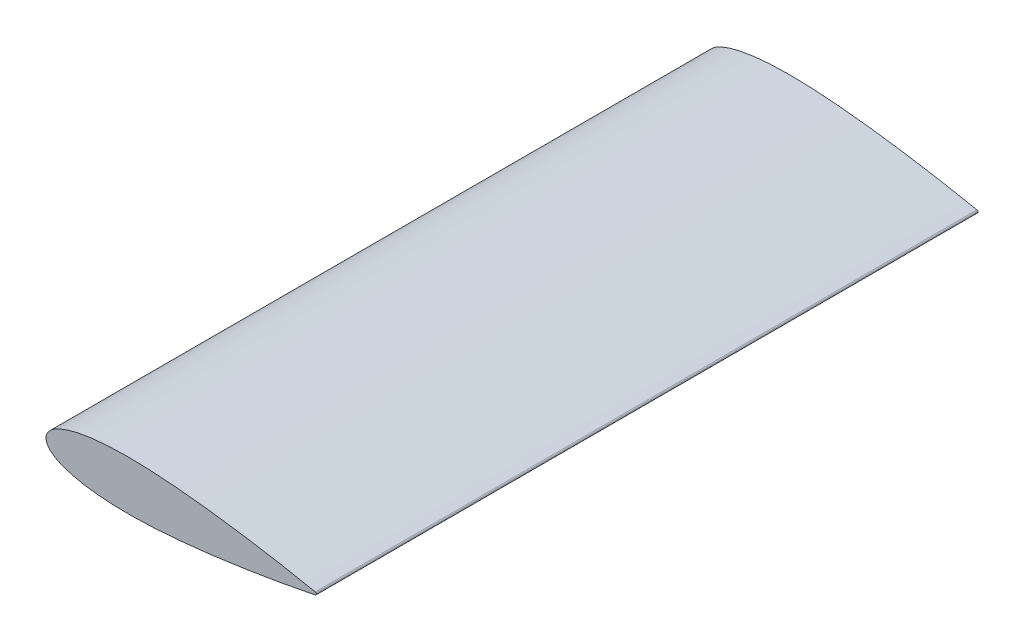
SolidWorks part; units mm, degrees
material "Polyurethane Foam Rigid"
ref_plane "Front Plane" through (0, 0, 0) normal (0, 0, 1) x (1, 0, 0)
ref_plane "Top Plane" through (0, 0, 0) normal (0, 1, 0) x (1, 0, 0)
ref_plane "Right Plane" through (0, 0, 0) normal (1, 0, 0) x (0, 0, -1)
curve "Curve1"
  spline degree 3 poles (0.9998, 0, 0) (1.0001, 0, 0) (0.9998, 0, 0) (0.9995, 0.0001, 0) (0.9989, 0.0002, 0) (0.9982, 0.0004, 0) (0.9972, 0.0006, 0) (0.996, 0.0009, 0) (0.9946, 0.0012, 0) (0.9929, 0.0015, 0) (0.9911, 0.0019, 0) (0.989, 0.0023, 0) (0.9867, 0.0028, 0) (0.9842, 0.0033, 0) (0.9815, 0.0039, 0) (0.9786, 0.0045, 0) (0.9755, 0.0051, 0) (0.9721, 0.0058, 0) (0.9686, 0.0065, 0) (0.9648, 0.0073, 0) (0.9609, 0.0081, 0) (0.9567, 0.009, 0) (0.9523, 0.0098, 0) (0.9478, 0.0107, 0) (0.943, 0.0117, 0) (0.9381, 0.0127, 0) (0.9329, 0.0137, 0) (0.9276, 0.0147, 0) (0.9221, 0.0158, 0) (0.9164, 0.0169, 0) (0.9105, 0.018, 0) (0.9045, 0.0192, 0) (0.8982, 0.0204, 0) (0.8918, 0.0216, 0) (0.8852, 0.0228, 0) (0.8784, 0.024, 0) (0.8715, 0.0253, 0) (0.8644, 0.0266, 0) (0.8572, 0.0279, 0) (0.8498, 0.0292, 0) (0.8422, 0.0306, 0) (0.8345, 0.0319, 0) (0.8267, 0.0333, 0) (0.8187, 0.0347, 0) (0.8105, 0.0361, 0) (0.8023, 0.0375, 0) (0.7939, 0.0389, 0) (0.7853, 0.0403, 0) (0.7767, 0.0417, 0) (0.7679, 0.0431, 0) (0.759, 0.0446, 0) (0.75, 0.046, 0) (0.7408, 0.0474, 0) (0.7316, 0.0489, 0) (0.7223, 0.0503, 0) (0.7129, 0.0517, 0) (0.7033, 0.0531, 0) (0.6937, 0.0546, 0) (0.684, 0.056, 0) (0.6743, 0.0574, 0) (0.6644, 0.0588, 0) (0.6545, 0.0601, 0) (0.6445, 0.0615, 0) (0.6344, 0.0629, 0) (0.6243, 0.0642, 0) (0.6142, 0.0655, 0) (0.6039, 0.0668, 0) (0.5937, 0.0681, 0) (0.5834, 0.0694, 0) (0.573, 0.0706, 0) (0.5627, 0.0718, 0) (0.5523, 0.073, 0) (0.5418, 0.0742, 0) (0.5314, 0.0753, 0) (0.5209, 0.0764, 0) (0.5105, 0.0774, 0) (0.5, 0.0785, 0) (0.4895, 0.0795, 0) (0.4791, 0.0804, 0) (0.4686, 0.0813, 0) (0.4582, 0.0822, 0) (0.4477, 0.083, 0) (0.4373, 0.0838, 0) (0.427, 0.0846, 0) (0.4166, 0.0853, 0) (0.4063, 0.0859, 0) (0.3961, 0.0865, 0) (0.3858, 0.0871, 0) (0.3757, 0.0876, 0) (0.3656, 0.088, 0) (0.3555, 0.0884, 0) (0.3455, 0.0887, 0) (0.3356, 0.089, 0) (0.3257, 0.0892, 0) (0.316, 0.0894, 0) (0.3063, 0.0894, 0) (0.2967, 0.0895, 0) (0.2871, 0.0894, 0) (0.2777, 0.0893, 0) (0.2684, 0.0892, 0) (0.2592, 0.089, 0) (0.25, 0.0887, 0) (0.241, 0.0883, 0) (0.2321, 0.0879, 0) (0.2233, 0.0874, 0) (0.2147, 0.0868, 0) (0.2061, 0.0862, 0) (0.1977, 0.0855, 0) (0.1895, 0.0847, 0) (0.1813, 0.0839, 0) (0.1733, 0.083, 0) (0.1655, 0.0821, 0) (0.1578, 0.081, 0) (0.1502, 0.0799, 0) (0.1428, 0.0788, 0) (0.1356, 0.0776, 0) (0.1285, 0.0763, 0) (0.1215, 0.0749, 0) (0.1148, 0.0735, 0) (0.1082, 0.072, 0) (0.1018, 0.0705, 0) (0.0955, 0.0689, 0) (0.0895, 0.0673, 0) (0.0836, 0.0656, 0) (0.0779, 0.0638, 0) (0.0724, 0.062, 0) (0.067, 0.0601, 0) (0.0619, 0.0582, 0) (0.0569, 0.0562, 0) (0.0522, 0.0542, 0) (0.0476, 0.0522, 0) (0.0433, 0.05, 0) (0.0391, 0.0479, 0) (0.0351, 0.0457, 0) (0.0314, 0.0434, 0) (0.0278, 0.0412, 0) (0.0245, 0.0388, 0) (0.0214, 0.0365, 0) (0.0184, 0.0341, 0) (0.0157, 0.0317, 0) (0.0132, 0.0292, 0) (0.0109, 0.0267, 0) (0.0089, 0.0241, 0) (0.007, 0.0216, 0) (0.0053, 0.019, 0) (0.0039, 0.0164, 0) (0.0027, 0.0137, 0) (0.0017, 0.011, 0) (0.001, 0.0083, 0) (0.0004, 0.0056, 0) (0.0001, 0.0028, 0) (0, 0, 0) (0.0001, -0.0028, 0) (0.0004, -0.0056, 0) (0.001, -0.0083, 0) (0.0017, -0.011, 0) (0.0027, -0.0137, 0) (0.0039, -0.0164, 0) (0.0053, -0.019, 0) (0.007, -0.0216, 0) (0.0089, -0.0241, 0) (0.0109, -0.0267, 0) (0.0132, -0.0292, 0) (0.0157, -0.0317, 0) (0.0184, -0.0341, 0) (0.0214, -0.0365, 0) (0.0245, -0.0388, 0) (0.0278, -0.0412, 0) (0.0314, -0.0434, 0) (0.0351, -0.0457, 0) (0.0391, -0.0479, 0) (0.0433, -0.05, 0) (0.0476, -0.0522, 0) (0.0522, -0.0542, 0) (0.0569, -0.0562, 0) (0.0619, -0.0582, 0) (0.067, -0.0601, 0) (0.0724, -0.062, 0) (0.0779, -0.0638, 0) (0.0836, -0.0656, 0) (0.0895, -0.0673, 0) (0.0955, -0.0689, 0) (0.1018, -0.0705, 0) (0.1082, -0.072, 0) (0.1148, -0.0735, 0) (0.1215, -0.0749, 0) (0.1285, -0.0763, 0) (0.1356, -0.0776, 0) (0.1428, -0.0788, 0) (0.1502, -0.0799, 0) (0.1578, -0.081, 0) (0.1655, -0.0821, 0) (0.1733, -0.083, 0) (0.1813, -0.0839, 0) (0.1895, -0.0847, 0) (0.1977, -0.0855, 0) (0.2061, -0.0862, 0) (0.2147, -0.0868, 0) (0.2233, -0.0874, 0) (0.2321, -0.0879, 0) (0.241, -0.0883, 0) (0.25, -0.0887, 0) (0.2592, -0.089, 0) (0.2684, -0.0892, 0) (0.2777, -0.0893, 0) (0.2871, -0.0894, 0) (0.2967, -0.0895, 0) (0.3063, -0.0894, 0) (0.316, -0.0894, 0) (0.3257, -0.0892, 0) (0.3356, -0.089, 0) (0.3455, -0.0887, 0) (0.3555, -0.0884, 0) (0.3656, -0.088, 0) (0.3757, -0.0876, 0) (0.3858, -0.0871, 0) (0.3961, -0.0865, 0) (0.4063, -0.0859, 0) (0.4166, -0.0853, 0) (0.427, -0.0846, 0) (0.4373, -0.0838, 0) (0.4477, -0.083, 0) (0.4582, -0.0822, 0) (0.4686, -0.0813, 0) (0.4791, -0.0804, 0) (0.4895, -0.0795, 0) (0.5, -0.0785, 0) (0.5105, -0.0774, 0) (0.5209, -0.0764, 0) (0.5314, -0.0753, 0) (0.5418, -0.0742, 0) (0.5523, -0.073, 0) (0.5627, -0.0718, 0) (0.573, -0.0706, 0) (0.5834, -0.0694, 0) (0.5937, -0.0681, 0) (0.6039, -0.0668, 0) (0.6142, -0.0655, 0) (0.6243, -0.0642, 0) (0.6344, -0.0629, 0) (0.6445, -0.0615, 0) (0.6545, -0.0601, 0) (0.6644, -0.0588, 0) (0.6743, -0.0574, 0) (0.684, -0.056, 0) (0.6937, -0.0546, 0) (0.7033, -0.0531, 0) (0.7129, -0.0517, 0) (0.7223, -0.0503, 0) (0.7316, -0.0489, 0) (0.7408, -0.0474, 0) (0.75, -0.046, 0) (0.759, -0.0446, 0) (0.7679, -0.0431, 0) (0.7767, -0.0417, 0) (0.7853, -0.0403, 0) (0.7939, -0.0389, 0) (0.8023, -0.0375, 0) (0.8105, -0.0361, 0) (0.8187, -0.0347, 0) (0.8267, -0.0333, 0) (0.8345, -0.0319, 0) (0.8422, -0.0306, 0) (0.8498, -0.0292, 0) (0.8572, -0.0279, 0) (0.8644, -0.0266, 0) (0.8715, -0.0253, 0) (0.8784, -0.024, 0) (0.8852, -0.0228, 0) (0.8918, -0.0216, 0) (0.8982, -0.0204, 0) (0.9045, -0.0192, 0) (0.9105, -0.018, 0) (0.9164, -0.0169, 0) (0.9221, -0.0158, 0) (0.9276, -0.0147, 0) (0.9329, -0.0137, 0) (0.9381, -0.0127, 0) (0.943, -0.0117, 0) (0.9478, -0.0107, 0) (0.9523, -0.0098, 0) (0.9567, -0.009, 0) (0.9609, -0.0081, 0) (0.9648, -0.0073, 0) (0.9686, -0.0065, 0) (0.9721, -0.0058, 0) (0.9755, -0.0051, 0) (0.9786, -0.0045, 0) (0.9815, -0.0039, 0) (0.9842, -0.0033, 0) (0.9867, -0.0028, 0) (0.989, -0.0023, 0) (0.9911, -0.0019, 0) (0.9929, -0.0015, 0) (0.9946, -0.0012, 0) (0.996, -0.0009, 0) (0.9972, -0.0006, 0) (0.9982, -0.0004, 0) (0.9989, -0.0002, 0) (0.9995, -0.0001, 0) (0.9998, 0, 0) (1.0001, 0, 0) (0.9998, 0, 0) knots -0.000486 -0.000216 -0.000054 0 0.000054 0.000216 0.000486 0.000863 0.001349 0.001941 0.002641 0.003447 0.00436 0.005379 0.006503 0.007732 0.009066 0.010503 0.012043 0.013685 0.01543 0.017274 0.019219 0.021263 0.023405 0.025644 0.027978 0.030408 0.032932 0.035548 0.038256 0.041054 0.04394 0.046915 0.049975 0.053121 0.05635 0.059661 0.063052 0.066522 0.07007 0.073693 0.077391 0.08116 0.085001 0.088911 0.092888 0.09693 0.101036 0.105204 0.109431 0.113717 0.118059 0.122455 0.126904 0.131403 0.135949 0.140543 0.14518 0.149859 0.154579 0.159336 0.164129 0.168955 0.173814 0.178701 0.183616 0.188555 0.193518 0.198501 0.203502 0.20852 0.213551 0.218594 0.223647 0.228706 0.233771 0.238839 0.243907 0.248973 0.254036 0.259092 0.26414 0.269178 0.274203 0.279214 0.284207 0.289181 0.294134 0.299064 0.303968 0.308845 0.313692 0.318508 0.323291 0.328038 0.332747 0.337418 0.342047 0.346633 0.351175 0.35567 0.360116 0.364513 0.368858 0.37315 0.377387 0.381568 0.38569 0.389754 0.393756 0.397696 0.401573 0.405385 0.409131 0.412809 0.41642 0.41996 0.42343 0.426829 0.430155 0.433407 0.436586 0.439689 0.442717 0.445669 0.448545 0.451343 0.454064 0.456707 0.459273 0.461761 0.464171 0.466505 0.468761 0.470942 0.473048 0.47508 0.47704 0.478929 0.480749 0.482504 0.484195 0.485826 0.487402 0.488926 0.490404 0.491842 0.493245 0.49462 0.495975 0.497318 0.498657 0.5 0.501343 0.502682 0.504025 0.50538 0.506755 0.508158 0.509596 0.511074 0.512598 0.514174 0.515805 0.517496 0.519251 0.521071 0.52296 0.52492 0.526952 0.529058 0.531239 0.533495 0.535829 0.538239 0.540727 0.543293 0.545936 0.548657 0.551455 0.554331 0.557283 0.560311 0.563414 0.566593 0.569845 0.573171 0.57657 0.58004 0.58358 0.587191 0.590869 0.594615 0.598427 0.602304 0.606244 0.610246 0.61431 0.618432 0.622613 0.62685 0.631142 0.635487 0.639884 0.64433 0.648825 0.653367 0.657953 0.662582 0.667253 0.671962 0.676709 0.681492 0.686308 0.691155 0.696032 0.700936 0.705866 0.710819 0.715793 0.720786 0.725797 0.730822 0.73586 0.740908 0.745964 0.751027 0.756093 0.761161 0.766229 0.771294 0.776353 0.781406 0.786449 0.79148 0.796498 0.801499 0.806482 0.811445 0.816384 0.821299 0.826186 0.831045 0.835871 0.840664 0.845421 0.850141 0.85482 0.859457 0.864051 0.868597 0.873096 0.877545 0.881941 0.886283 0.890569 0.894796 0.898964 0.90307 0.907112 0.911089 0.914999 0.91884 0.922609 0.926307 0.92993 0.933478 0.936948 0.940339 0.94365 0.946879 0.950025 0.953085 0.95606 0.958946 0.961744 0.964452 0.967068 0.969592 0.972022 0.974356 0.976595 0.978737 0.980781 0.982726 0.98457 0.986315 0.987957 0.989497 0.990934 0.992268 0.993497 0.994621 0.99564 0.996553 0.997359 0.998059 0.998651 0.999137 0.999514 0.999784 0.999946 1 1.000054 1.000216 1.000486 periodic
sketch "Sketch1" plane through (0, 0, 0) normal (0, 0, 1) x (1, 0, 0)
  line L0 (500, 0) -> (0, 0) construction
  line L1 (0, 0) -> (0, 42.6879) construction
  spline S1 degree 3 poles (499.8824, -0.0194) (500.0294, 0) (499.8824, 0.0194) (499.761, 0.0543) (499.4625, 0.1124) (499.0899, 0.1937) (498.593, 0.2981) (497.9928, 0.4253) (497.2818, 0.5753) (496.4631, 0.7479) (495.5359, 0.9429) (494.5012, 1.16) (493.3592, 1.3989) (492.1105, 1.6595) (490.7555, 1.9413) (489.295, 2.244) (487.7295, 2.5673) (486.0597, 2.9109) (484.2864, 3.2742) (482.4103, 3.6569) (480.4323, 4.0585) (478.3532, 4.4786) (476.1739, 4.9168) (473.8954, 5.3725) (471.5188, 5.8452) (469.0449, 6.3344) (466.475, 6.8397) (463.8101, 7.3605) (461.0514, 7.8961) (458.2002, 8.4462) (455.2576, 9.0101) (452.2251, 9.5872) (449.1038, 10.177) (445.8951, 10.7789) (442.6006, 11.3923) (439.2215, 12.0167) (435.7595, 12.6514) (432.216, 13.2958) (428.5925, 13.9493) (424.8908, 14.6114) (421.1123, 15.2814) (417.2587, 15.9587) (413.3318, 16.6427) (409.3332, 17.3328) (405.2648, 18.0283) (401.1282, 18.7287) (396.9254, 19.4333) (392.6581, 20.1415) (388.3283, 20.8527) (383.9377, 21.5662) (379.4884, 22.2814) (374.9824, 22.9977) (370.4215, 23.7144) (365.8077, 24.4308) (361.1432, 25.1463) (356.4299, 25.8603) (351.67, 26.572) (346.8654, 27.2807) (342.0184, 27.9859) (337.131, 28.6868) (332.2054, 29.3827) (327.2437, 30.0728) (322.2481, 30.7566) (317.2209, 31.4332) (312.1642, 32.102) (307.0802, 32.7621) (301.9711, 33.4128) (296.8393, 34.0535) (291.6869, 34.6832) (286.5163, 35.3013) (281.3296, 35.907) (276.1291, 36.4994) (270.9173, 37.0778) (265.6962, 37.6415) (260.4682, 38.1895) (255.2357, 38.7211) (250.0009, 39.2356) (244.766, 39.7321) (239.5335, 40.2097) (234.3055, 40.6678) (229.0844, 41.1056) (223.8725, 41.5221) (218.6721, 41.9167) (213.4854, 42.2886) (208.3147, 42.6371) (203.1622, 42.9613) (198.0304, 43.2606) (192.9213, 43.5343) (187.8372, 43.7816) (182.7804, 44.0019) (177.7531, 44.1945) (172.7575, 44.3588) (167.7957, 44.4943) (162.87, 44.6003) (157.9825, 44.6762) (153.1354, 44.7217) (148.3307, 44.7361) (143.5706, 44.7192) (138.8572, 44.6704) (134.1926, 44.5894) (129.5787, 44.4759) (125.0176, 44.3295) (120.5114, 44.1502) (116.0619, 43.9375) (111.6712, 43.6915) (107.3412, 43.412) (103.0737, 43.0988) (98.8706, 42.7521) (94.7338, 42.3718) (90.6651, 41.9579) (86.6663, 41.5107) (82.7391, 41.0302) (78.8853, 40.5167) (75.1065, 39.9703) (71.4044, 39.3915) (67.7806, 38.7805) (64.2367, 38.1376) (60.7743, 37.4633) (57.3948, 36.758) (54.0998, 36.0223) (50.8907, 35.2565) (47.7689, 34.4613) (44.7357, 33.6371) (41.7926, 32.7847) (38.9407, 31.9045) (36.1813, 30.9972) (33.5157, 30.0636) (30.9449, 29.1041) (28.4702, 28.1196) (26.0925, 27.1107) (23.813, 26.078) (21.6325, 25.0223) (19.5521, 23.9442) (17.5726, 22.8444) (15.695, 21.7236) (13.9199, 20.5824) (12.2482, 19.4215) (10.6806, 18.2415) (9.2178, 17.0429) (7.8604, 15.8264) (6.609, 14.5925) (5.4642, 13.3416) (4.4265, 12.0743) (3.4965, 10.7909) (2.6745, 9.4919) (1.9611, 8.1778) (1.3567, 6.8488) (0.8617, 5.5055) (0.4765, 4.1481) (0.2013, 2.7771) (0.0363, 1.3928) (-0.0182, 0) (0.0363, -1.3928) (0.2013, -2.7771) (0.4765, -4.1481) (0.8617, -5.5055) (1.3567, -6.8488) (1.9611, -8.1778) (2.6745, -9.4919) (3.4965, -10.7909) (4.4265, -12.0743) (5.4642, -13.3416) (6.609, -14.5925) (7.8604, -15.8264) (9.2178, -17.0429) (10.6806, -18.2415) (12.2482, -19.4215) (13.9199, -20.5824) (15.695, -21.7236) (17.5726, -22.8444) (19.5521, -23.9442) (21.6325, -25.0223) (23.813, -26.078) (26.0925, -27.1107) (28.4702, -28.1196) (30.9449, -29.1041) (33.5157, -30.0636) (36.1813, -30.9972) (38.9407, -31.9045) (41.7926, -32.7847) (44.7357, -33.6371) (47.7689, -34.4613) (50.8907, -35.2565) (54.0998, -36.0223) (57.3948, -36.758) (60.7743, -37.4633) (64.2367, -38.1376) (67.7806, -38.7805) (71.4044, -39.3915) (75.1065, -39.9703) (78.8853, -40.5167) (82.7391, -41.0302) (86.6663, -41.5107) (90.6651, -41.9579) (94.7338, -42.3718) (98.8706, -42.7521) (103.0737, -43.0988) (107.3412, -43.412) (111.6712, -43.6915) (116.0619, -43.9375) (120.5114, -44.1502) (125.0176, -44.3295) (129.5787, -44.4759) (134.1926, -44.5894) (138.8572, -44.6704) (143.5706, -44.7192) (148.3307, -44.7361) (153.1354, -44.7217) (157.9825, -44.6762) (162.87, -44.6003) (167.7957, -44.4943) (172.7575, -44.3588) (177.7531, -44.1945) (182.7804, -44.0019) (187.8372, -43.7816) (192.9213, -43.5343) (198.0304, -43.2606) (203.1622, -42.9613) (208.3147, -42.6371) (213.4854, -42.2886) (218.6721, -41.9167) (223.8725, -41.5221) (229.0844, -41.1056) (234.3055, -40.6678) (239.5335, -40.2097) (244.766, -39.7321) (250.0009, -39.2356) (255.2357, -38.7211) (260.4682, -38.1895) (265.6962, -37.6415) (270.9173, -37.0778) (276.1291, -36.4994) (281.3296, -35.907) (286.5163, -35.3013) (291.6869, -34.6832) (296.8393, -34.0535) (301.9711, -33.4128) (307.0802, -32.7621) (312.1642, -32.102) (317.2209, -31.4332) (322.2481, -30.7566) (327.2437, -30.0728) (332.2054, -29.3827) (337.131, -28.6868) (342.0184, -27.9859) (346.8654, -27.2807) (351.67, -26.572) (356.4299, -25.8603) (361.1432, -25.1463) (365.8077, -24.4308) (370.4215, -23.7144) (374.9824, -22.9977) (379.4884, -22.2814) (383.9377, -21.5662) (388.3283, -20.8527) (392.6581, -20.1415) (396.9254, -19.4333) (401.1282, -18.7287) (405.2648, -18.0283) (409.3332, -17.3328) (413.3318, -16.6427) (417.2587, -15.9587) (421.1123, -15.2814) (424.8908, -14.6114) (428.5925, -13.9493) (432.216, -13.2958) (435.7595, -12.6514) (439.2215, -12.0167) (442.6006, -11.3923) (445.8951, -10.7789) (449.1038, -10.177) (452.2251, -9.5872) (455.2576, -9.0101) (458.2002, -8.4462) (461.0514, -7.8961) (463.8101, -7.3605) (466.475, -6.8397) (469.0449, -6.3344) (471.5188, -5.8452) (473.8954, -5.3725) (476.1739, -4.9168) (478.3532, -4.4786) (480.4323, -4.0585) (482.4103, -3.6569) (484.2864, -3.2742) (486.0597, -2.9109) (487.7295, -2.5673) (489.295, -2.244) (490.7555, -1.9413) (492.1105, -1.6595) (493.3592, -1.3989) (494.5012, -1.16) (495.5359, -0.9429) (496.4631, -0.7479) (497.2818, -0.5753) (497.9928, -0.4253) (498.593, -0.2981) (499.0899, -0.1937) (499.4625, -0.1124) (499.761, -0.0543) (499.8824, -0.0194) (500.0294, 0) (499.8824, 0.0194) knots -0.000486 -0.000216 -0.000054 0 0.000054 0.000216 0.000486 0.000863 0.001349 0.001941 0.002641 0.003447 0.00436 0.005379 0.006503 0.007732 0.009066 0.010503 0.012043 0.013685 0.01543 0.017274 0.019219 0.021263 0.023405 0.025644 0.027978 0.030408 0.032932 0.035548 0.038256 0.041054 0.04394 0.046915 0.049975 0.053121 0.05635 0.059661 0.063052 0.066522 0.07007 0.073693 0.077391 0.08116 0.085001 0.088911 0.092888 0.09693 0.101036 0.105204 0.109431 0.113717 0.118059 0.122455 0.126904 0.131403 0.135949 0.140543 0.14518 0.149859 0.154579 0.159336 0.164129 0.168955 0.173814 0.178701 0.183616 0.188555 0.193518 0.198501 0.203502 0.20852 0.213551 0.218594 0.223647 0.228706 0.233771 0.238839 0.243907 0.248973 0.254036 0.259092 0.26414 0.269178 0.274203 0.279214 0.284207 0.289181 0.294134 0.299064 0.303968 0.308845 0.313692 0.318508 0.323291 0.328038 0.332747 0.337418 0.342047 0.346633 0.351175 0.35567 0.360116 0.364513 0.368858 0.37315 0.377387 0.381568 0.38569 0.389754 0.393756 0.397696 0.401573 0.405385 0.409131 0.412809 0.41642 0.41996 0.42343 0.426829 0.430155 0.433407 0.436586 0.439689 0.442717 0.445669 0.448545 0.451343 0.454064 0.456707 0.459273 0.461761 0.464171 0.466505 0.468761 0.470942 0.473048 0.47508 0.47704 0.478929 0.480749 0.482504 0.484195 0.485826 0.487402 0.488926 0.490404 0.491842 0.493245 0.49462 0.495975 0.497318 0.498657 0.5 0.501343 0.502682 0.504025 0.50538 0.506755 0.508158 0.509596 0.511074 0.512598 0.514174 0.515805 0.517496 0.519251 0.521071 0.52296 0.52492 0.526952 0.529058 0.531239 0.533495 0.535829 0.538239 0.540727 0.543293 0.545936 0.548657 0.551455 0.554331 0.557283 0.560311 0.563414 0.566593 0.569845 0.573171 0.57657 0.58004 0.58358 0.587191 0.590869 0.594615 0.598427 0.602304 0.606244 0.610246 0.61431 0.618432 0.622613 0.62685 0.631142 0.635487 0.639884 0.64433 0.648825 0.653367 0.657953 0.662582 0.667253 0.671962 0.676709 0.681492 0.686308 0.691155 0.696032 0.700936 0.705866 0.710819 0.715793 0.720786 0.725797 0.730822 0.73586 0.740908 0.745964 0.751027 0.756093 0.761161 0.766229 0.771294 0.776353 0.781406 0.786449 0.79148 0.796498 0.801499 0.806482 0.811445 0.816384 0.821299 0.826186 0.831045 0.835871 0.840664 0.845421 0.850141 0.85482 0.859457 0.864051 0.868597 0.873096 0.877545 0.881941 0.886283 0.890569 0.894796 0.898964 0.90307 0.907112 0.911089 0.914999 0.91884 0.922609 0.926307 0.92993 0.933478 0.936948 0.940339 0.94365 0.946879 0.950025 0.953085 0.95606 0.958946 0.961744 0.964452 0.967068 0.969592 0.972022 0.974356 0.976595 0.978737 0.980781 0.982726 0.98457 0.986315 0.987957 0.989497 0.990934 0.992268 0.993497 0.994621 0.99564 0.996553 0.997359 0.998059 0.998651 0.999137 0.999514 0.999784 0.999946 1 1.000054 1.000216 1.000486 only from (500, 0) to (500, 0)
  dimension "D1" = 500
sketch "Sketch2" plane through (0, 0, 0) normal (0, 0, 1) x (1, 0, 0)
  line L0 (500, 0) -> (0, 0) construction
  line L1 (500, 0) -> (0, 0) construction
  circle A2 centre (487.7998, 0) radius 2.5
  spline S0 degree 3 poles (499.8824, -0.0194) (500.0294, 0) (499.8824, 0.0194) (499.761, 0.0543) (499.4625, 0.1124) (499.0899, 0.1937) (498.593, 0.2981) (497.9928, 0.4253) (497.2818, 0.5753) (496.4631, 0.7479) (495.5359, 0.9429) (494.5012, 1.16) (493.3592, 1.3989) (492.1105, 1.6595) (490.7555, 1.9413) (489.295, 2.244) (487.7295, 2.5673) (486.0597, 2.9109) (484.2864, 3.2742) (482.4103, 3.6569) (480.4323, 4.0585) (478.3532, 4.4786) (476.1739, 4.9168) (473.8954, 5.3725) (471.5188, 5.8452) (469.0449, 6.3344) (466.475, 6.8397) (463.8101, 7.3605) (461.0514, 7.8961) (458.2002, 8.4462) (455.2576, 9.0101) (452.2251, 9.5872) (449.1038, 10.177) (445.8951, 10.7789) (442.6006, 11.3923) (439.2215, 12.0167) (435.7595, 12.6514) (432.216, 13.2958) (428.5925, 13.9493) (424.8908, 14.6114) (421.1123, 15.2814) (417.2587, 15.9587) (413.3318, 16.6427) (409.3332, 17.3328) (405.2648, 18.0283) (401.1282, 18.7287) (396.9254, 19.4333) (392.6581, 20.1415) (388.3283, 20.8527) (383.9377, 21.5662) (379.4884, 22.2814) (374.9824, 22.9977) (370.4215, 23.7144) (365.8077, 24.4308) (361.1432, 25.1463) (356.4299, 25.8603) (351.67, 26.572) (346.8654, 27.2807) (342.0184, 27.9859) (337.131, 28.6868) (332.2054, 29.3827) (327.2437, 30.0728) (322.2481, 30.7566) (317.2209, 31.4332) (312.1642, 32.102) (307.0802, 32.7621) (301.9711, 33.4128) (296.8393, 34.0535) (291.6869, 34.6832) (286.5163, 35.3013) (281.3296, 35.907) (276.1291, 36.4994) (270.9173, 37.0778) (265.6962, 37.6415) (260.4682, 38.1895) (255.2357, 38.7211) (250.0009, 39.2356) (244.766, 39.7321) (239.5335, 40.2097) (234.3055, 40.6678) (229.0844, 41.1056) (223.8725, 41.5221) (218.6721, 41.9167) (213.4854, 42.2886) (208.3147, 42.6371) (203.1622, 42.9613) (198.0304, 43.2606) (192.9213, 43.5343) (187.8372, 43.7816) (182.7804, 44.0019) (177.7531, 44.1945) (172.7575, 44.3588) (167.7957, 44.4943) (162.87, 44.6003) (157.9825, 44.6762) (153.1354, 44.7217) (148.3307, 44.7361) (143.5706, 44.7192) (138.8572, 44.6704) (134.1926, 44.5894) (129.5787, 44.4759) (125.0176, 44.3295) (120.5114, 44.1502) (116.0619, 43.9375) (111.6712, 43.6915) (107.3412, 43.412) (103.0737, 43.0988) (98.8706, 42.7521) (94.7338, 42.3718) (90.6651, 41.9579) (86.6663, 41.5107) (82.7391, 41.0302) (78.8853, 40.5167) (75.1065, 39.9703) (71.4044, 39.3915) (67.7806, 38.7805) (64.2367, 38.1376) (60.7743, 37.4633) (57.3948, 36.758) (54.0998, 36.0223) (50.8907, 35.2565) (47.7689, 34.4613) (44.7357, 33.6371) (41.7926, 32.7847) (38.9407, 31.9045) (36.1813, 30.9972) (33.5157, 30.0636) (30.9449, 29.1041) (28.4702, 28.1196) (26.0925, 27.1107) (23.813, 26.078) (21.6325, 25.0223) (19.5521, 23.9442) (17.5726, 22.8444) (15.695, 21.7236) (13.9199, 20.5824) (12.2482, 19.4215) (10.6806, 18.2415) (9.2178, 17.0429) (7.8604, 15.8264) (6.609, 14.5925) (5.4642, 13.3416) (4.4265, 12.0743) (3.4965, 10.7909) (2.6745, 9.4919) (1.9611, 8.1778) (1.3567, 6.8488) (0.8617, 5.5055) (0.4765, 4.1481) (0.2013, 2.7771) (0.0363, 1.3928) (-0.0182, 0) (0.0363, -1.3928) (0.2013, -2.7771) (0.4765, -4.1481) (0.8617, -5.5055) (1.3567, -6.8488) (1.9611, -8.1778) (2.6745, -9.4919) (3.4965, -10.7909) (4.4265, -12.0743) (5.4642, -13.3416) (6.609, -14.5925) (7.8604, -15.8264) (9.2178, -17.0429) (10.6806, -18.2415) (12.2482, -19.4215) (13.9199, -20.5824) (15.695, -21.7236) (17.5726, -22.8444) (19.5521, -23.9442) (21.6325, -25.0223) (23.813, -26.078) (26.0925, -27.1107) (28.4702, -28.1196) (30.9449, -29.1041) (33.5157, -30.0636) (36.1813, -30.9972) (38.9407, -31.9045) (41.7926, -32.7847) (44.7357, -33.6371) (47.7689, -34.4613) (50.8907, -35.2565) (54.0998, -36.0223) (57.3948, -36.758) (60.7743, -37.4633) (64.2367, -38.1376) (67.7806, -38.7805) (71.4044, -39.3915) (75.1065, -39.9703) (78.8853, -40.5167) (82.7391, -41.0302) (86.6663, -41.5107) (90.6651, -41.9579) (94.7338, -42.3718) (98.8706, -42.7521) (103.0737, -43.0988) (107.3412, -43.412) (111.6712, -43.6915) (116.0619, -43.9375) (120.5114, -44.1502) (125.0176, -44.3295) (129.5787, -44.4759) (134.1926, -44.5894) (138.8572, -44.6704) (143.5706, -44.7192) (148.3307, -44.7361) (153.1354, -44.7217) (157.9825, -44.6762) (162.87, -44.6003) (167.7957, -44.4943) (172.7575, -44.3588) (177.7531, -44.1945) (182.7804, -44.0019) (187.8372, -43.7816) (192.9213, -43.5343) (198.0304, -43.2606) (203.1622, -42.9613) (208.3147, -42.6371) (213.4854, -42.2886) (218.6721, -41.9167) (223.8725, -41.5221) (229.0844, -41.1056) (234.3055, -40.6678) (239.5335, -40.2097) (244.766, -39.7321) (250.0009, -39.2356) (255.2357, -38.7211) (260.4682, -38.1895) (265.6962, -37.6415) (270.9173, -37.0778) (276.1291, -36.4994) (281.3296, -35.907) (286.5163, -35.3013) (291.6869, -34.6832) (296.8393, -34.0535) (301.9711, -33.4128) (307.0802, -32.7621) (312.1642, -32.102) (317.2209, -31.4332) (322.2481, -30.7566) (327.2437, -30.0728) (332.2054, -29.3827) (337.131, -28.6868) (342.0184, -27.9859) (346.8654, -27.2807) (351.67, -26.572) (356.4299, -25.8603) (361.1432, -25.1463) (365.8077, -24.4308) (370.4215, -23.7144) (374.9824, -22.9977) (379.4884, -22.2814) (383.9377, -21.5662) (388.3283, -20.8527) (392.6581, -20.1415) (396.9254, -19.4333) (401.1282, -18.7287) (405.2648, -18.0283) (409.3332, -17.3328) (413.3318, -16.6427) (417.2587, -15.9587) (421.1123, -15.2814) (424.8908, -14.6114) (428.5925, -13.9493) (432.216, -13.2958) (435.7595, -12.6514) (439.2215, -12.0167) (442.6006, -11.3923) (445.8951, -10.7789) (449.1038, -10.177) (452.2251, -9.5872) (455.2576, -9.0101) (458.2002, -8.4462) (461.0514, -7.8961) (463.8101, -7.3605) (466.475, -6.8397) (469.0449, -6.3344) (471.5188, -5.8452) (473.8954, -5.3725) (476.1739, -4.9168) (478.3532, -4.4786) (480.4323, -4.0585) (482.4103, -3.6569) (484.2864, -3.2742) (486.0597, -2.9109) (487.7295, -2.5673) (489.295, -2.244) (490.7555, -1.9413) (492.1105, -1.6595) (493.3592, -1.3989) (494.5012, -1.16) (495.5359, -0.9429) (496.4631, -0.7479) (497.2818, -0.5753) (497.9928, -0.4253) (498.593, -0.2981) (499.0899, -0.1937) (499.4625, -0.1124) (499.761, -0.0543) (499.8824, -0.0194) (500.0294, 0) (499.8824, 0.0194) knots -0.000486 -0.000216 -0.000054 0 0.000054 0.000216 0.000486 0.000863 0.001349 0.001941 0.002641 0.003447 0.00436 0.005379 0.006503 0.007732 0.009066 0.010503 0.012043 0.013685 0.01543 0.017274 0.019219 0.021263 0.023405 0.025644 0.027978 0.030408 0.032932 0.035548 0.038256 0.041054 0.04394 0.046915 0.049975 0.053121 0.05635 0.059661 0.063052 0.066522 0.07007 0.073693 0.077391 0.08116 0.085001 0.088911 0.092888 0.09693 0.101036 0.105204 0.109431 0.113717 0.118059 0.122455 0.126904 0.131403 0.135949 0.140543 0.14518 0.149859 0.154579 0.159336 0.164129 0.168955 0.173814 0.178701 0.183616 0.188555 0.193518 0.198501 0.203502 0.20852 0.213551 0.218594 0.223647 0.228706 0.233771 0.238839 0.243907 0.248973 0.254036 0.259092 0.26414 0.269178 0.274203 0.279214 0.284207 0.289181 0.294134 0.299064 0.303968 0.308845 0.313692 0.318508 0.323291 0.328038 0.332747 0.337418 0.342047 0.346633 0.351175 0.35567 0.360116 0.364513 0.368858 0.37315 0.377387 0.381568 0.38569 0.389754 0.393756 0.397696 0.401573 0.405385 0.409131 0.412809 0.41642 0.41996 0.42343 0.426829 0.430155 0.433407 0.436586 0.439689 0.442717 0.445669 0.448545 0.451343 0.454064 0.456707 0.459273 0.461761 0.464171 0.466505 0.468761 0.470942 0.473048 0.47508 0.47704 0.478929 0.480749 0.482504 0.484195 0.485826 0.487402 0.488926 0.490404 0.491842 0.493245 0.49462 0.495975 0.497318 0.498657 0.5 0.501343 0.502682 0.504025 0.50538 0.506755 0.508158 0.509596 0.511074 0.512598 0.514174 0.515805 0.517496 0.519251 0.521071 0.52296 0.52492 0.526952 0.529058 0.531239 0.533495 0.535829 0.538239 0.540727 0.543293 0.545936 0.548657 0.551455 0.554331 0.557283 0.560311 0.563414 0.566593 0.569845 0.573171 0.57657 0.58004 0.58358 0.587191 0.590869 0.594615 0.598427 0.602304 0.606244 0.610246 0.61431 0.618432 0.622613 0.62685 0.631142 0.635487 0.639884 0.64433 0.648825 0.653367 0.657953 0.662582 0.667253 0.671962 0.676709 0.681492 0.686308 0.691155 0.696032 0.700936 0.705866 0.710819 0.715793 0.720786 0.725797 0.730822 0.73586 0.740908 0.745964 0.751027 0.756093 0.761161 0.766229 0.771294 0.776353 0.781406 0.786449 0.79148 0.796498 0.801499 0.806482 0.811445 0.816384 0.821299 0.826186 0.831045 0.835871 0.840664 0.845421 0.850141 0.85482 0.859457 0.864051 0.868597 0.873096 0.877545 0.881941 0.886283 0.890569 0.894796 0.898964 0.90307 0.907112 0.911089 0.914999 0.91884 0.922609 0.926307 0.92993 0.933478 0.936948 0.940339 0.94365 0.946879 0.950025 0.953085 0.95606 0.958946 0.961744 0.964452 0.967068 0.969592 0.972022 0.974356 0.976595 0.978737 0.980781 0.982726 0.98457 0.986315 0.987957 0.989497 0.990934 0.992268 0.993497 0.994621 0.99564 0.996553 0.997359 0.998059 0.998651 0.999137 0.999514 0.999784 0.999946 1 1.000054 1.000216 1.000486 only from (500, 0) to (500, 0) construction
  spline S1 degree 3 poles (499.8824, -0.0194) (500.0294, 0) (499.8824, 0.0194) (499.761, 0.0543) (499.4625, 0.1124) (499.0899, 0.1937) (498.593, 0.2981) (497.9928, 0.4253) (497.2818, 0.5753) (496.4631, 0.7479) (495.5359, 0.9429) (494.5012, 1.16) (493.3592, 1.3989) (492.1105, 1.6595) (490.7555, 1.9413) (489.295, 2.244) (487.7295, 2.5673) (486.0597, 2.9109) (484.2864, 3.2742) (482.4103, 3.6569) (480.4323, 4.0585) (478.3532, 4.4786) (476.1739, 4.9168) (473.8954, 5.3725) (471.5188, 5.8452) (469.0449, 6.3344) (466.475, 6.8397) (463.8101, 7.3605) (461.0514, 7.8961) (458.2002, 8.4462) (455.2576, 9.0101) (452.2251, 9.5872) (449.1038, 10.177) (445.8951, 10.7789) (442.6006, 11.3923) (439.2215, 12.0167) (435.7595, 12.6514) (432.216, 13.2958) (428.5925, 13.9493) (424.8908, 14.6114) (421.1123, 15.2814) (417.2587, 15.9587) (413.3318, 16.6427) (409.3332, 17.3328) (405.2648, 18.0283) (401.1282, 18.7287) (396.9254, 19.4333) (392.6581, 20.1415) (388.3283, 20.8527) (383.9377, 21.5662) (379.4884, 22.2814) (374.9824, 22.9977) (370.4215, 23.7144) (365.8077, 24.4308) (361.1432, 25.1463) (356.4299, 25.8603) (351.67, 26.572) (346.8654, 27.2807) (342.0184, 27.9859) (337.131, 28.6868) (332.2054, 29.3827) (327.2437, 30.0728) (322.2481, 30.7566) (317.2209, 31.4332) (312.1642, 32.102) (307.0802, 32.7621) (301.9711, 33.4128) (296.8393, 34.0535) (291.6869, 34.6832) (286.5163, 35.3013) (281.3296, 35.907) (276.1291, 36.4994) (270.9173, 37.0778) (265.6962, 37.6415) (260.4682, 38.1895) (255.2357, 38.7211) (250.0009, 39.2356) (244.766, 39.7321) (239.5335, 40.2097) (234.3055, 40.6678) (229.0844, 41.1056) (223.8725, 41.5221) (218.6721, 41.9167) (213.4854, 42.2886) (208.3147, 42.6371) (203.1622, 42.9613) (198.0304, 43.2606) (192.9213, 43.5343) (187.8372, 43.7816) (182.7804, 44.0019) (177.7531, 44.1945) (172.7575, 44.3588) (167.7957, 44.4943) (162.87, 44.6003) (157.9825, 44.6762) (153.1354, 44.7217) (148.3307, 44.7361) (143.5706, 44.7192) (138.8572, 44.6704) (134.1926, 44.5894) (129.5787, 44.4759) (125.0176, 44.3295) (120.5114, 44.1502) (116.0619, 43.9375) (111.6712, 43.6915) (107.3412, 43.412) (103.0737, 43.0988) (98.8706, 42.7521) (94.7338, 42.3718) (90.6651, 41.9579) (86.6663, 41.5107) (82.7391, 41.0302) (78.8853, 40.5167) (75.1065, 39.9703) (71.4044, 39.3915) (67.7806, 38.7805) (64.2367, 38.1376) (60.7743, 37.4633) (57.3948, 36.758) (54.0998, 36.0223) (50.8907, 35.2565) (47.7689, 34.4613) (44.7357, 33.6371) (41.7926, 32.7847) (38.9407, 31.9045) (36.1813, 30.9972) (33.5157, 30.0636) (30.9449, 29.1041) (28.4702, 28.1196) (26.0925, 27.1107) (23.813, 26.078) (21.6325, 25.0223) (19.5521, 23.9442) (17.5726, 22.8444) (15.695, 21.7236) (13.9199, 20.5824) (12.2482, 19.4215) (10.6806, 18.2415) (9.2178, 17.0429) (7.8604, 15.8264) (6.609, 14.5925) (5.4642, 13.3416) (4.4265, 12.0743) (3.4965, 10.7909) (2.6745, 9.4919) (1.9611, 8.1778) (1.3567, 6.8488) (0.8617, 5.5055) (0.4765, 4.1481) (0.2013, 2.7771) (0.0363, 1.3928) (-0.0182, 0) (0.0363, -1.3928) (0.2013, -2.7771) (0.4765, -4.1481) (0.8617, -5.5055) (1.3567, -6.8488) (1.9611, -8.1778) (2.6745, -9.4919) (3.4965, -10.7909) (4.4265, -12.0743) (5.4642, -13.3416) (6.609, -14.5925) (7.8604, -15.8264) (9.2178, -17.0429) (10.6806, -18.2415) (12.2482, -19.4215) (13.9199, -20.5824) (15.695, -21.7236) (17.5726, -22.8444) (19.5521, -23.9442) (21.6325, -25.0223) (23.813, -26.078) (26.0925, -27.1107) (28.4702, -28.1196) (30.9449, -29.1041) (33.5157, -30.0636) (36.1813, -30.9972) (38.9407, -31.9045) (41.7926, -32.7847) (44.7357, -33.6371) (47.7689, -34.4613) (50.8907, -35.2565) (54.0998, -36.0223) (57.3948, -36.758) (60.7743, -37.4633) (64.2367, -38.1376) (67.7806, -38.7805) (71.4044, -39.3915) (75.1065, -39.9703) (78.8853, -40.5167) (82.7391, -41.0302) (86.6663, -41.5107) (90.6651, -41.9579) (94.7338, -42.3718) (98.8706, -42.7521) (103.0737, -43.0988) (107.3412, -43.412) (111.6712, -43.6915) (116.0619, -43.9375) (120.5114, -44.1502) (125.0176, -44.3295) (129.5787, -44.4759) (134.1926, -44.5894) (138.8572, -44.6704) (143.5706, -44.7192) (148.3307, -44.7361) (153.1354, -44.7217) (157.9825, -44.6762) (162.87, -44.6003) (167.7957, -44.4943) (172.7575, -44.3588) (177.7531, -44.1945) (182.7804, -44.0019) (187.8372, -43.7816) (192.9213, -43.5343) (198.0304, -43.2606) (203.1622, -42.9613) (208.3147, -42.6371) (213.4854, -42.2886) (218.6721, -41.9167) (223.8725, -41.5221) (229.0844, -41.1056) (234.3055, -40.6678) (239.5335, -40.2097) (244.766, -39.7321) (250.0009, -39.2356) (255.2357, -38.7211) (260.4682, -38.1895) (265.6962, -37.6415) (270.9173, -37.0778) (276.1291, -36.4994) (281.3296, -35.907) (286.5163, -35.3013) (291.6869, -34.6832) (296.8393, -34.0535) (301.9711, -33.4128) (307.0802, -32.7621) (312.1642, -32.102) (317.2209, -31.4332) (322.2481, -30.7566) (327.2437, -30.0728) (332.2054, -29.3827) (337.131, -28.6868) (342.0184, -27.9859) (346.8654, -27.2807) (351.67, -26.572) (356.4299, -25.8603) (361.1432, -25.1463) (365.8077, -24.4308) (370.4215, -23.7144) (374.9824, -22.9977) (379.4884, -22.2814) (383.9377, -21.5662) (388.3283, -20.8527) (392.6581, -20.1415) (396.9254, -19.4333) (401.1282, -18.7287) (405.2648, -18.0283) (409.3332, -17.3328) (413.3318, -16.6427) (417.2587, -15.9587) (421.1123, -15.2814) (424.8908, -14.6114) (428.5925, -13.9493) (432.216, -13.2958) (435.7595, -12.6514) (439.2215, -12.0167) (442.6006, -11.3923) (445.8951, -10.7789) (449.1038, -10.177) (452.2251, -9.5872) (455.2576, -9.0101) (458.2002, -8.4462) (461.0514, -7.8961) (463.8101, -7.3605) (466.475, -6.8397) (469.0449, -6.3344) (471.5188, -5.8452) (473.8954, -5.3725) (476.1739, -4.9168) (478.3532, -4.4786) (480.4323, -4.0585) (482.4103, -3.6569) (484.2864, -3.2742) (486.0597, -2.9109) (487.7295, -2.5673) (489.295, -2.244) (490.7555, -1.9413) (492.1105, -1.6595) (493.3592, -1.3989) (494.5012, -1.16) (495.5359, -0.9429) (496.4631, -0.7479) (497.2818, -0.5753) (497.9928, -0.4253) (498.593, -0.2981) (499.0899, -0.1937) (499.4625, -0.1124) (499.761, -0.0543) (499.8824, -0.0194) (500.0294, 0) (499.8824, 0.0194) knots -0.000486 -0.000216 -0.000054 0 0.000054 0.000216 0.000486 0.000863 0.001349 0.001941 0.002641 0.003447 0.00436 0.005379 0.006503 0.007732 0.009066 0.010503 0.012043 0.013685 0.01543 0.017274 0.019219 0.021263 0.023405 0.025644 0.027978 0.030408 0.032932 0.035548 0.038256 0.041054 0.04394 0.046915 0.049975 0.053121 0.05635 0.059661 0.063052 0.066522 0.07007 0.073693 0.077391 0.08116 0.085001 0.088911 0.092888 0.09693 0.101036 0.105204 0.109431 0.113717 0.118059 0.122455 0.126904 0.131403 0.135949 0.140543 0.14518 0.149859 0.154579 0.159336 0.164129 0.168955 0.173814 0.178701 0.183616 0.188555 0.193518 0.198501 0.203502 0.20852 0.213551 0.218594 0.223647 0.228706 0.233771 0.238839 0.243907 0.248973 0.254036 0.259092 0.26414 0.269178 0.274203 0.279214 0.284207 0.289181 0.294134 0.299064 0.303968 0.308845 0.313692 0.318508 0.323291 0.328038 0.332747 0.337418 0.342047 0.346633 0.351175 0.35567 0.360116 0.364513 0.368858 0.37315 0.377387 0.381568 0.38569 0.389754 0.393756 0.397696 0.401573 0.405385 0.409131 0.412809 0.41642 0.41996 0.42343 0.426829 0.430155 0.433407 0.436586 0.439689 0.442717 0.445669 0.448545 0.451343 0.454064 0.456707 0.459273 0.461761 0.464171 0.466505 0.468761 0.470942 0.473048 0.47508 0.47704 0.478929 0.480749 0.482504 0.484195 0.485826 0.487402 0.488926 0.490404 0.491842 0.493245 0.49462 0.495975 0.497318 0.498657 0.5 0.501343 0.502682 0.504025 0.50538 0.506755 0.508158 0.509596 0.511074 0.512598 0.514174 0.515805 0.517496 0.519251 0.521071 0.52296 0.52492 0.526952 0.529058 0.531239 0.533495 0.535829 0.538239 0.540727 0.543293 0.545936 0.548657 0.551455 0.554331 0.557283 0.560311 0.563414 0.566593 0.569845 0.573171 0.57657 0.58004 0.58358 0.587191 0.590869 0.594615 0.598427 0.602304 0.606244 0.610246 0.61431 0.618432 0.622613 0.62685 0.631142 0.635487 0.639884 0.64433 0.648825 0.653367 0.657953 0.662582 0.667253 0.671962 0.676709 0.681492 0.686308 0.691155 0.696032 0.700936 0.705866 0.710819 0.715793 0.720786 0.725797 0.730822 0.73586 0.740908 0.745964 0.751027 0.756093 0.761161 0.766229 0.771294 0.776353 0.781406 0.786449 0.79148 0.796498 0.801499 0.806482 0.811445 0.816384 0.821299 0.826186 0.831045 0.835871 0.840664 0.845421 0.850141 0.85482 0.859457 0.864051 0.868597 0.873096 0.877545 0.881941 0.886283 0.890569 0.894796 0.898964 0.90307 0.907112 0.911089 0.914999 0.91884 0.922609 0.926307 0.92993 0.933478 0.936948 0.940339 0.94365 0.946879 0.950025 0.953085 0.95606 0.958946 0.961744 0.964452 0.967068 0.969592 0.972022 0.974356 0.976595 0.978737 0.980781 0.982726 0.98457 0.986315 0.987957 0.989497 0.990934 0.992268 0.993497 0.994621 0.99564 0.996553 0.997359 0.998059 0.998651 0.999137 0.999514 0.999784 0.999946 1 1.000054 1.000216 1.000486 only from (500, 0) to (500, 0)
  dimension "D1" = 5
extrude "Boss-Extrude1" add sketch "Sketch2" along normal blind 1200 contours L1 A2 S1 | A2 L1 S1 | A2 L1 | L1 A2
